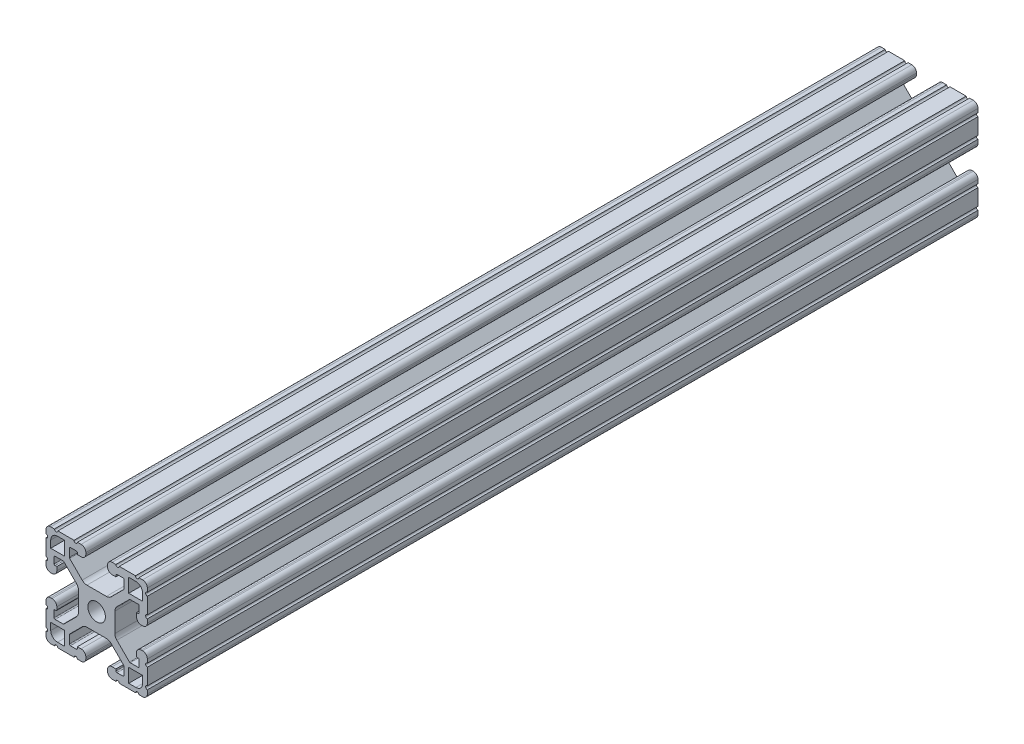
SolidWorks part; units mm, degrees
ref_plane "Front Plane" through (0, 0, 0) normal (0, 0, 1) x (1, 0, 0)
ref_plane "Top Plane" through (0, 0, 0) normal (0, 1, 0) x (1, 0, 0)
ref_plane "Right Plane" through (0, 0, 0) normal (1, 0, 0) x (0, 0, -1)
sketch "Sketch1" plane through (0, 0, 0) normal (0, 0, 1) x (1, 0, 0)
  line L0 (0, -19.05) -> (0, 19.05) construction
  line L1 (19.05, 0) -> (-19.05, 0) construction
  line L2 (4.064, 19.05) -> (-4.064, 19.05) construction
  line L3 (0, -6.858) -> (0, 6.858) construction
  line L4 (-4.064, 19.05) -> (-4.064, 14.986) construction
  line L5 (19.05, -10.287) -> (19.05, 10.287) construction
  line L6 (0, -3.302) -> (0, 3.302) construction
  point P4 (0, 0)
  point P8 (0, 0)
  point P11 (0, 19.05)
  point P14 (0, 0)
  point P18 (19.05, 0)
  point P21 (0, 0)
  dimension "Rail Width" = 38.1
  dimension "Rail Height" = 38.1
  dimension "T-Slot Width" = 8.128
  dimension "Thickness" = 4.064
  dimension "Opening Width" = 20.574
  dimension "Center Hole Diameter" = 6.604
  dimension "Slot Depth" = 12.192
sketch "Sketch2" plane through (0, 0, 0) normal (1, 0, 0) x (0, 0, -1)
  line L0 (-156.21, 0) -> (156.21, 0) construction
  line L1 (0, 19.05) -> (0, -19.05) construction
  line L2 (-25.4, 19.05) -> (25.4, 19.05) construction
  line L4 (3048, -19.05) -> (-3048, -19.05) construction
  point P0 (105.41, 0)
  point P3 (-105.41, 0)
  point P4 (0, 0)
  dimension "D1" = 50.8
  dimension "Rep Length" = 312.42
  dimension "D2" = 50.8
  dimension "Length Range [Min]" = 50.8
  dimension "Length Range [Max]" = 6096
sketch "Sketch3" plane through (0, 0, 0) normal (0, 0, 1) x (1, 0, 0)
  line L1 (19.05, -19.05) -> (-19.05, -19.05)
  line L2 (19.05, -19.05) -> (19.05, 19.05)
  line L3 (19.05, 19.05) -> (-19.05, 19.05)
  line L4 (-19.05, -19.05) -> (-19.05, 19.05)
  line L5 (19.05, -19.05) -> (-19.05, 19.05) construction
  line L6 (19.05, 19.05) -> (-19.05, -19.05) construction
  point P0 (0, 0)
extrude "Boss-Extrude1" add sketch "Sketch3" along normal up to vertex (156.21 mm away) and the other way up to vertex (156.21 mm away) up to point (0, 0, 156.21) other way up to point (0, 0, -156.21)
sketch "Sketch4" plane through (0, 0, 156.21) normal (0, 0, 1) x (1, 0, 0)
  line L4 (4.064, 14.986) -> (4.064, 19.05)
  line L5 (7.239, 14.986) -> (4.064, 14.986)
  line L6 (19.05, 0) -> (-19.05, 0) construction
  line L7 (4.7027, 6.858) -> (-4.7027, 6.858)
  line L8 (-4.7027, 6.858) -> (-10.287, 12.4423)
  line L37 (-19.05, 19.05) -> (-19.05, -19.05) construction
  line L38 (-19.05, -19.05) -> (19.05, -19.05) construction
  line L39 (-10.287, 12.4423) -> (-10.287, 16.002)
  line L40 (-10.287, 16.002) -> (-7.239, 16.002)
  line L41 (-7.239, 16.002) -> (-7.239, 14.986)
  line L42 (-7.239, 14.986) -> (-4.064, 14.986)
  line L43 (-4.064, 14.986) -> (-4.064, 19.05)
  line L44 (-4.064, 19.05) -> (4.064, 19.05)
  line L45 (0, 19.05) -> (0, 0) construction
  line L46 (-19.05, 19.05) -> (0, 0) construction
  line L47 (7.239, 16.002) -> (7.239, 14.986)
  line L48 (10.287, 16.002) -> (7.239, 16.002)
  line L49 (10.287, 12.4423) -> (10.287, 16.002)
  line L50 (4.7027, 6.858) -> (10.287, 12.4423)
  line L51 (-19.05, 0) -> (19.05, 0) construction
  line L52 (4.7027, -6.858) -> (10.287, -12.4423)
  line L53 (10.287, -12.4423) -> (10.287, -16.002)
  line L54 (10.287, -16.002) -> (7.239, -16.002)
  line L55 (7.239, -16.002) -> (7.239, -14.986)
  line L56 (-4.064, -19.05) -> (4.064, -19.05)
  line L57 (-4.064, -14.986) -> (-4.064, -19.05)
  line L58 (-7.239, -14.986) -> (-4.064, -14.986)
  line L59 (-7.239, -16.002) -> (-7.239, -14.986)
  line L60 (-10.287, -16.002) -> (-7.239, -16.002)
  line L61 (-10.287, -12.4423) -> (-10.287, -16.002)
  line L62 (-4.7027, -6.858) -> (-10.287, -12.4423)
  line L63 (4.7027, -6.858) -> (-4.7027, -6.858)
  line L64 (7.239, -14.986) -> (4.064, -14.986)
  line L65 (4.064, -14.986) -> (4.064, -19.05)
  line L66 (-6.858, -4.7027) -> (-12.4423, -10.287)
  line L67 (-12.4423, -10.287) -> (-16.002, -10.287)
  line L68 (-16.002, -10.287) -> (-16.002, -7.239)
  line L69 (-16.002, -7.239) -> (-14.986, -7.239)
  line L70 (-19.05, 4.064) -> (-19.05, -4.064)
  line L71 (-14.986, 4.064) -> (-19.05, 4.064)
  line L72 (-14.986, 7.239) -> (-14.986, 4.064)
  line L73 (-16.002, 7.239) -> (-14.986, 7.239)
  line L74 (-16.002, 10.287) -> (-16.002, 7.239)
  line L75 (-12.4423, 10.287) -> (-16.002, 10.287)
  line L76 (-6.858, 4.7027) -> (-12.4423, 10.287)
  line L77 (-6.858, -4.7027) -> (-6.858, 4.7027)
  line L78 (-14.986, -7.239) -> (-14.986, -4.064)
  line L79 (-14.986, -4.064) -> (-19.05, -4.064)
  line L80 (14.986, -4.064) -> (19.05, -4.064)
  line L81 (14.986, -7.239) -> (14.986, -4.064)
  line L82 (6.858, -4.7027) -> (6.858, 4.7027)
  line L83 (6.858, 4.7027) -> (12.4423, 10.287)
  line L84 (12.4423, 10.287) -> (16.002, 10.287)
  line L85 (16.002, 10.287) -> (16.002, 7.239)
  line L86 (16.002, 7.239) -> (14.986, 7.239)
  line L87 (14.986, 7.239) -> (14.986, 4.064)
  line L88 (14.986, 4.064) -> (19.05, 4.064)
  line L89 (19.05, 4.064) -> (19.05, -4.064)
  line L90 (16.002, -7.239) -> (14.986, -7.239)
  line L91 (16.002, -10.287) -> (16.002, -7.239)
  line L92 (12.4423, -10.287) -> (16.002, -10.287)
  line L93 (6.858, -4.7027) -> (12.4423, -10.287)
  line L94 (19.05, -19.05) -> (19.05, 19.05) construction
  line L95 (12.065, 17.272) -> (17.272, 17.272)
  line L96 (12.065, 17.272) -> (12.065, 12.065)
  line L97 (12.065, 12.065) -> (17.272, 12.065)
  line L98 (17.272, 17.272) -> (17.272, 12.065)
  line L99 (19.05, 19.05) -> (-19.05, 19.05) construction
  line L100 (17.272, -17.272) -> (17.272, -12.065)
  line L101 (12.065, -17.272) -> (17.272, -17.272)
  line L102 (12.065, -17.272) -> (12.065, -12.065)
  line L103 (12.065, -12.065) -> (17.272, -12.065)
  line L104 (-17.272, 17.272) -> (-17.272, 12.065)
  line L105 (-12.065, 12.065) -> (-17.272, 12.065)
  line L106 (-12.065, 17.272) -> (-12.065, 12.065)
  line L107 (-12.065, 17.272) -> (-17.272, 17.272)
  line L108 (-12.065, -12.065) -> (-17.272, -12.065)
  line L109 (-12.065, -17.272) -> (-12.065, -12.065)
  line L110 (-12.065, -17.272) -> (-17.272, -17.272)
  line L111 (-17.272, -17.272) -> (-17.272, -12.065)
  circle A5 centre (0, 0) radius 3.302
  point P21 (0, 6.858)
  point P23 (0, -6.858)
  point P38 (-6.858, 0)
  point P53 (6.858, 0)
  dimension "D1" = 20.574
  dimension "D2" = 3.048
  dimension "D3" = 3.048
  dimension "D4" = 3.048
  dimension "D5" = 1.778
  dimension "D6" = 1.778
  dimension "D7" = 1.778
extrude "Cut-Extrude1" cut sketch "Sketch4" against normal through all
sketch "Sketch5" plane through (0, 0, 156.21) normal (0, 0, 1) x (1, 0, 0)
  line L4 (-4.064, 19.05) -> (-19.05, 19.05) construction
  line L26 (-19.05, 19.05) -> (-19.05, 4.064) construction
  line L27 (-15.875, 19.05) -> (-14.605, 19.05)
  line L28 (-8.509, 19.05) -> (-7.239, 19.05)
  line L29 (-19.05, 15.875) -> (-19.05, 14.605)
  line L30 (-19.05, 8.509) -> (-19.05, 7.239)
  line L31 (8.509, 19.05) -> (7.239, 19.05)
  line L32 (15.875, 19.05) -> (14.605, 19.05)
  line L33 (19.05, 15.875) -> (19.05, 14.605)
  line L34 (19.05, 8.509) -> (19.05, 7.239)
  line L35 (19.05, -8.509) -> (19.05, -7.239)
  line L36 (19.05, -15.875) -> (19.05, -14.605)
  line L37 (15.875, -19.05) -> (14.605, -19.05)
  line L38 (8.509, -19.05) -> (7.239, -19.05)
  line L39 (-8.509, -19.05) -> (-7.239, -19.05)
  line L40 (-15.875, -19.05) -> (-14.605, -19.05)
  line L41 (-19.05, -15.875) -> (-19.05, -14.605)
  line L42 (-19.05, -8.509) -> (-19.05, -7.239)
  line L43 (19.05, 19.05) -> (4.064, 19.05) construction
  line L44 (19.05, 4.064) -> (19.05, 19.05) construction
  line L48 (-14.986, 4.064) -> (-19.05, 4.064) construction
  line L49 (-4.064, 14.986) -> (-4.064, 19.05) construction
  arc A8 (-15.875, 19.05) -> (-14.605, 19.05) centre (-15.24, 19.05) ccw
  arc A9 (-8.509, 19.05) -> (-7.239, 19.05) centre (-7.874, 19.05) ccw
  arc A10 (-19.05, 14.605) -> (-19.05, 15.875) centre (-19.05, 15.24) ccw
  arc A11 (-19.05, 7.239) -> (-19.05, 8.509) centre (-19.05, 7.874) ccw
  arc A12 (7.239, 19.05) -> (8.509, 19.05) centre (7.874, 19.05) ccw
  arc A13 (14.605, 19.05) -> (15.875, 19.05) centre (15.24, 19.05) ccw
  arc A14 (19.05, 15.875) -> (19.05, 14.605) centre (19.05, 15.24) ccw
  arc A15 (19.05, 8.509) -> (19.05, 7.239) centre (19.05, 7.874) ccw
  arc A16 (19.05, -7.239) -> (19.05, -8.509) centre (19.05, -7.874) ccw
  arc A17 (19.05, -14.605) -> (19.05, -15.875) centre (19.05, -15.24) ccw
  arc A18 (15.875, -19.05) -> (14.605, -19.05) centre (15.24, -19.05) ccw
  arc A19 (8.509, -19.05) -> (7.239, -19.05) centre (7.874, -19.05) ccw
  arc A20 (-7.239, -19.05) -> (-8.509, -19.05) centre (-7.874, -19.05) ccw
  arc A21 (-14.605, -19.05) -> (-15.875, -19.05) centre (-15.24, -19.05) ccw
  arc A22 (-19.05, -15.875) -> (-19.05, -14.605) centre (-19.05, -15.24) ccw
  arc A23 (-19.05, -8.509) -> (-19.05, -7.239) centre (-19.05, -7.874) ccw
  dimension "D2" = 0.635
  dimension "D4" = 3.81
  dimension "D5" = 3.81
  dimension "D1" = 3.81
  dimension "D3" = 3.81
  dimension "D7" = 4
extrude "Cut-Extrude2" cut sketch "Sketch5" against normal through all
fillet "Fillet1" radius 2.54 12 edges at (-6.858, 4.7027, 0) (-6.858, -4.7027, 0) (4.7027, -6.858, 0) (-4.7027, -6.858, 0) (6.858, -4.7027, 0) (6.858, 4.7027, 0) (4.7027, 6.858, 0) (-4.7027, 6.858, 0) (-17.272, 17.272, 0) (17.272, 17.272, 0) (17.272, -17.272, 0) (-17.272, -17.272, 0)
fillet "Fillet2" radius 1.778 20 edges at (19.05, -19.05, 0) (19.05, 19.05, 0) (-19.05, -19.05, 0) (-19.05, 19.05, 0) (-14.986, 4.064, 0) (-19.05, 4.064, 0) (-19.05, -4.064, 0) (-14.986, -4.064, 0) (-4.064, -19.05, 0) (-4.064, -14.986, 0) (4.064, -14.986, 0) (4.064, -19.05, 0) (19.05, -4.064, 0) (14.986, -4.064, 0) (19.05, 4.064, 0) (14.986, 4.064, 0) (4.064, 14.986, 0) (4.064, 19.05, 0) (-4.064, 19.05, 0) (-4.064, 14.986, 0)
fillet "Fillet3" radius 0.3969 24 edges at (-14.986, -7.239, 0) (-16.002, -10.287, 0) (-12.4423, -10.287, 0) (-12.4423, 10.287, 0) (-16.002, 7.239, 0) (-16.002, 10.287, 0) (-10.287, 12.4423, 0) (-7.239, 16.002, 0) (-10.287, 16.002, 0) (10.287, 16.002, 0) (7.239, 16.002, 0) (10.287, 12.4423, 0) (16.002, 10.287, 0) (12.4423, 10.287, 0) (16.002, 7.239, 0) (16.002, -7.239, 0) (16.002, -10.287, 0) (12.4423, -10.287, 0) (10.287, -12.4423, 0) (10.287, -16.002, 0) (7.239, -16.002, 0) (-7.239, -16.002, 0) (-10.287, -12.4423, 0) (-10.287, -16.002, 0)
equation "\"D4@Sketch5\"=\"D3@Sketch5\""
equation "\"D5@Sketch5\"=\"D4@Sketch5\""
equation "\"D1@Sketch4\"=\"Opening Width@Sketch1\""
